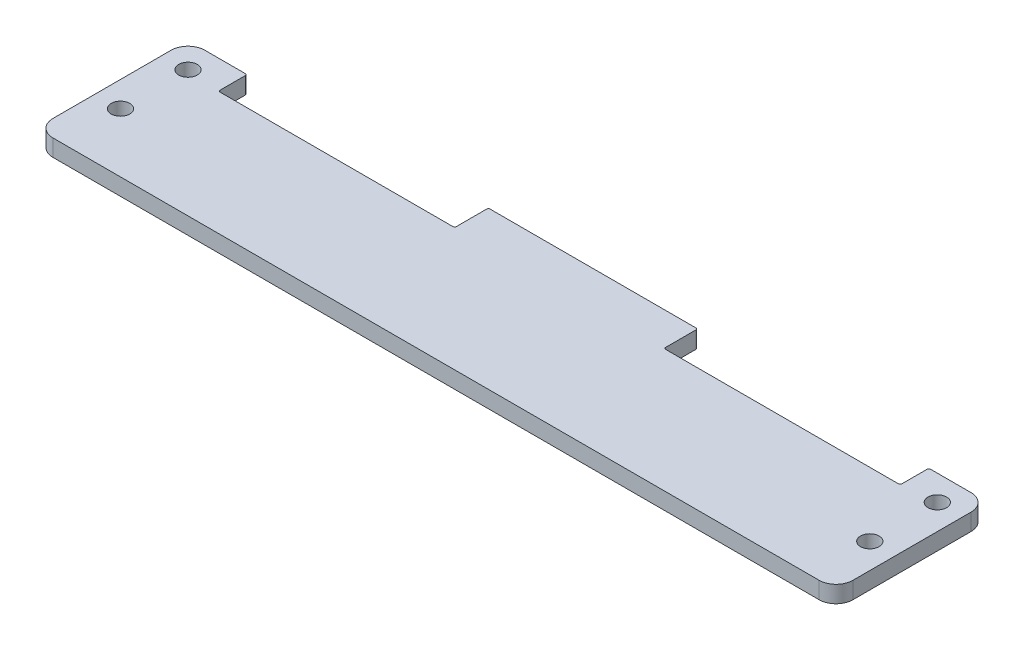
SolidWorks part; units mm, degrees
material "ABS"
ref_plane "Front Plane" through (0, 0, 0) normal (0, 0, 1) x (1, 0, 0)
ref_plane "Top Plane" through (0, 0, 0) normal (0, 1, 0) x (1, 0, 0)
ref_plane "Right Plane" through (0, 0, 0) normal (1, 0, 0) x (0, 0, -1)
sketch "Sketch1" plane through (0, 0, 0) normal (0, 1, 0) x (1, 0, 0)
  line L0 (-118.5, 0) -> (118.5, 0)
  line L1 (118.5, 0) -> (118.5, 45)
  line L2 (101, 36.5) -> (31, 36.5)
  line L3 (31, 36.5) -> (31, 46.5)
  line L4 (31, 46.5) -> (-31, 46.5)
  line L5 (-31, 46.5) -> (-31, 36.5)
  line L6 (-31, 36.5) -> (-101, 36.5)
  line L9 (-118.5, 45) -> (-118.5, 0)
  line L10 (0, -55) -> (0, 55) construction
  line L11 (-111, 17.5) -> (111, 17.5) construction
  line L12 (111, 17.5) -> (111, 37.5) construction
  line L13 (-111, 17.5) -> (-111, 37.5) construction
  line L14 (-101, 36.5) -> (-101, 45)
  line L15 (-101, 45) -> (-118.5, 45)
  line L16 (101, 36.5) -> (101, 45)
  line L17 (101, 45) -> (118.5, 45)
  point P2 (0, 46.5)
  point P3 (0, 0)
  point P10 (95, 44.5573)
  point P16 (0, 17.5)
  dimension "D2" = 62
  dimension "D3" = 10
  dimension "D4" = 7.5
  dimension "D7" = 222
  dimension "D8" = 20
  dimension "D9" = 17.5
  dimension "D10" = 10
  dimension "D11" = 7.5
  dimension "D12" = 19
extrude "Boss-Extrude1" add sketch "Sketch1" against normal blind 5
hole_wizard "M5 Clearance Hole1" positions "Sketch4" profile "Sketch5" hole size "M5" standard "ANSI Metric" end condition up to next
sketch "Sketch4" plane through (0, 0, 0) normal (0, 1, 0) x (1, 0, 0)
  point P0 (-111, 37.5)
  point P3 (-111, 17.5)
  point P6 (111, 37.5)
  point P9 (111, 17.5)
sketch "Sketch5" plane through (-111, 0, -37.5) normal (1, 0, 0) x (0, 0, 1)
  line L0 (0, 0) -> (0, 5)
  line L1 (0, 5) -> (2.75, 5)
  line L2 (2.75, 5) -> (2.75, 0)
  line L5 (2.75, 0) -> (0, 0)
  line L11 (0, -6.35) -> (0, 107.95) construction
  dimension "Thru Hole Dia." = 5.5
  dimension "Thru Hole Depth" = 5
fillet "Fillet1" radius 5 4 edges at (-118.5, -2.5, -45) (118.5, -2.5, -45) (118.5, -2.5, 0) (-118.5, -2.5, 0)
fillet "Fillet2" radius 0.5 8 edges at (101, -2.5, -45) (101, -2.5, -36.5) (31, -2.5, -36.5) (31, -2.5, -46.5) (-31, -2.5, -46.5) (-31, -2.5, -36.5) (-101, -2.5, -45) (-101, -2.5, -36.5)
